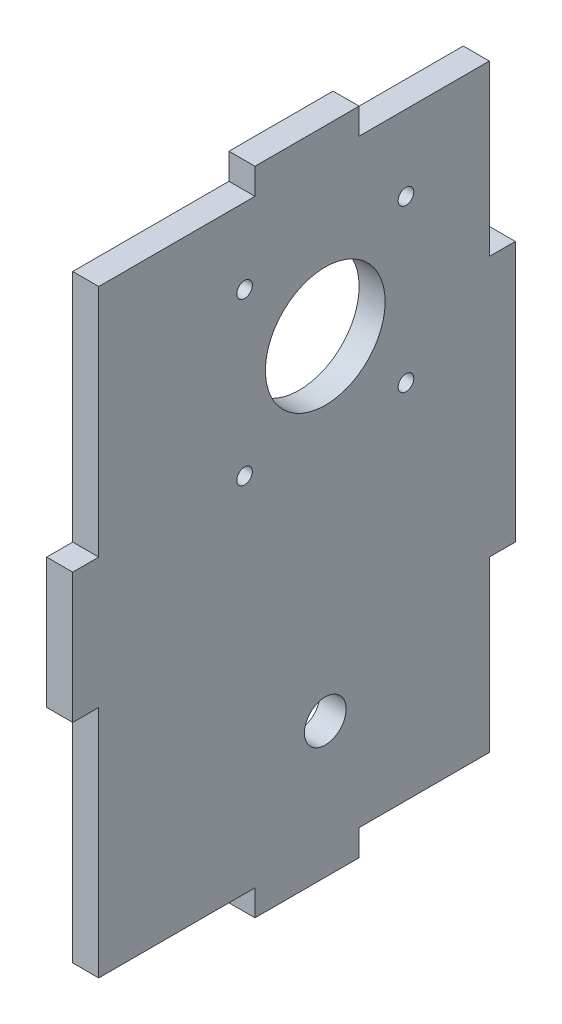
SolidWorks part; units mm, degrees
ref_plane "前视基准面" through (0, 0, 0) normal (0, 0, 1) x (1, 0, 0)
ref_plane "上视基准面" through (0, 0, 0) normal (0, 1, 0) x (1, 0, 0)
ref_plane "右视基准面" through (0, 0, 0) normal (1, 0, 0) x (0, 0, -1)
sketch "草图1" plane through (0, 0, 0) normal (1, 0, 0) x (0, 0, -1)
  line L0 (-80, 70) -> (-80, 115)
  line L1 (-5, 0) -> (-30, 0)
  line L2 (0, 32.5) -> (0, 82.5)
  line L3 (-5, 115) -> (-30, 115)
  line L4 (-80, 0) -> (-80, 45)
  line L5 (-36.5, 135.817) -> (-36.5, -49.0196) construction
  line L6 (-30, 0) -> (-30, -5)
  line L7 (-30, -5) -> (-50, -5)
  line L8 (-50, 0) -> (-50, -5)
  line L9 (-50, 0) -> (-80, 0)
  line L10 (-30, 115) -> (-30, 120)
  line L11 (-30, 120) -> (-50, 120)
  line L12 (-50, 115) -> (-50, 120)
  line L13 (-80, 70) -> (-85, 70)
  line L14 (-50, 115) -> (-80, 115)
  line L15 (-80, 45) -> (-85, 45)
  line L16 (-85, 70) -> (-85, 45)
  line L17 (0, 82.5) -> (-5, 82.5)
  line L20 (-5, 82.5) -> (-5, 115)
  line L21 (0, 32.5) -> (-5, 32.5)
  line L24 (-5, 32.5) -> (-5, 0)
  circle A0 centre (-36.5, 21) radius 4
  circle A1 centre (-36.5, 85) radius 11.5
  circle A2 centre (-52, 100.5) radius 1.5
  circle A3 centre (-21, 100.5) radius 1.5
  circle A4 centre (-21, 69.5) radius 1.5
  circle A5 centre (-52, 69.5) radius 1.5
  point P17 (-82.5, 45)
  dimension "D18" = 15.5
  dimension "D27" = 3
  dimension "D28" = 23
  dimension "D2" = 80
  dimension "D3" = 5
  dimension "D4" = 5
  dimension "D5" = 5
  dimension "D6" = 20
  dimension "D7" = 20
  dimension "D8" = 25
  dimension "D9" = 30
  dimension "D10" = 30
  dimension "D11" = 45
  dimension "D12" = 5
  dimension "D13" = 5
  dimension "D14" = 50
  dimension "D15" = 32.5
  dimension "D16" = 115
  dimension "D17" = 36.5
  dimension "D19" = 0
  dimension "D20" = 15.5
  dimension "D21" = 15.5
  dimension "D22" = 15.5
  dimension "D23" = 31
  dimension "D24" = 31
  dimension "D25" = 15.5
  dimension "D26" = 15.5
  dimension "D29" = 30
  dimension "D31" = 21
extrude "凸台-拉伸1" add sketch "草图1" along normal blind 5
